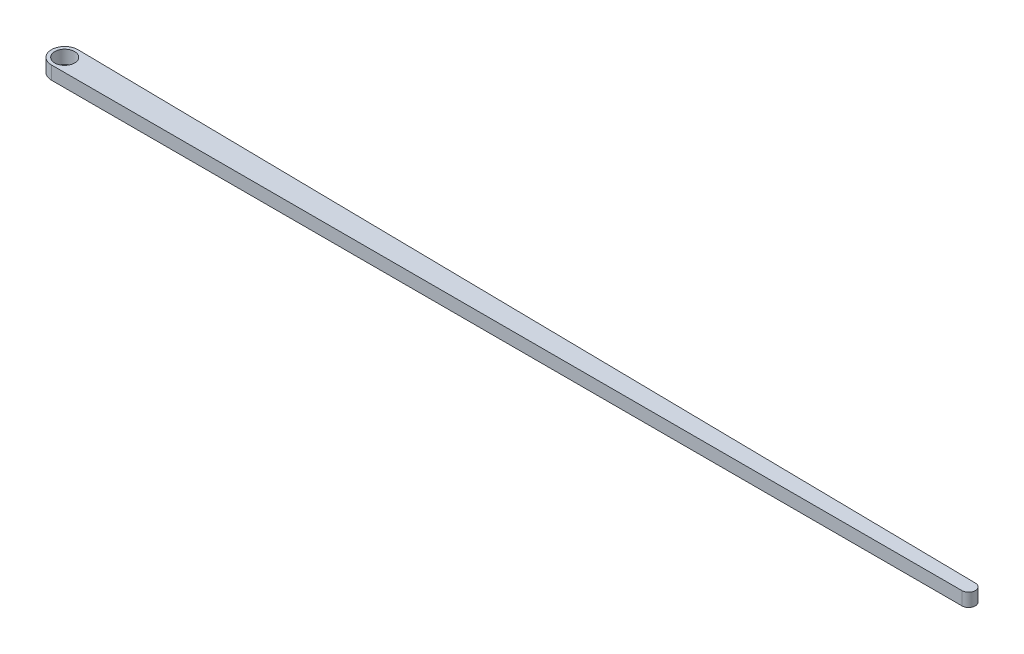
SolidWorks part; units mm, degrees
ref_plane "Front Plane" through (0, 0, 0) normal (0, 0, 1) x (1, 0, 0)
ref_plane "Top Plane" through (0, 0, 0) normal (0, 1, 0) x (1, 0, 0)
ref_plane "Right Plane" through (0, 0, 0) normal (1, 0, 0) x (0, 0, -1)
sketch "Sketch1" plane through (0, 0, 0) normal (0, 1, 0) x (1, 0, 0)
  line L0 (0, 0) -> (2200, 0)
  line L1 (0, 0) -> (0, 64)
  line L2 (0, 64) -> (2200, 32)
  line L3 (2200, 32) -> (2200, 0)
  circle A0 centre (0, 32) radius 32
  circle A1 centre (0, 32) radius 24
  circle A2 centre (2200, 16) radius 16
  dimension "D4" = 48
  dimension "D1" = 2200
  dimension "D2" = 64
  dimension "D3" = 32
extrude "Boss-Extrude1" add sketch "Sketch1" along normal blind 32 contours A1 L1 A0 | A1 L1 A0 L2 | A2 L2 A0 L0 | L3 A2 | L3 A2
